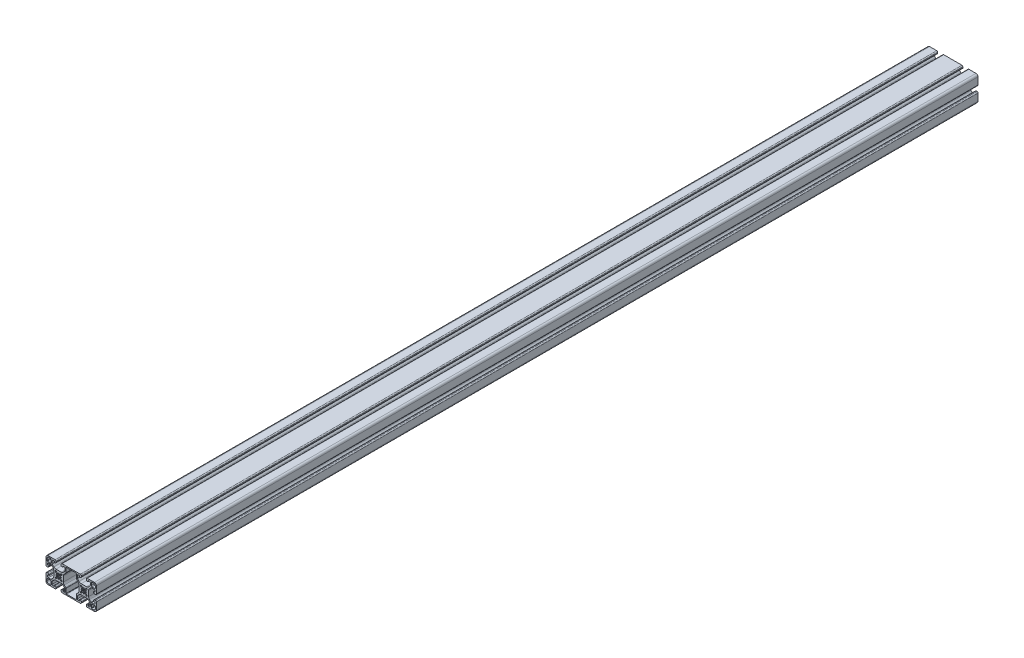
SolidWorks part; units mm, degrees
material "6105-T5 Aluminum"
ref_plane "Front Plane" through (0, 0, 0) normal (0, 0, 1) x (1, 0, 0)
ref_plane "Top Plane" through (0, 0, 0) normal (0, 1, 0) x (1, 0, 0)
ref_plane "Right Plane" through (0, 0, 0) normal (1, 0, 0) x (0, 0, -1)
sketch "Sketch1" plane through (0, 0, 0) normal (0, 0, 1) x (1, 0, 0)
  line L0 (-44, -18.4848) -> (-44, -17.255)
  line L1 (-46.474, -15.685) -> (-45.57, -15.685)
  line L2 (-56.83, -20) -> (-45.569, -20)
  line L3 (-46.855, -17.119) -> (-46.855, -16.066)
  line L4 (-60, -16.83) -> (-60, -5.57)
  line L5 (-49.015, -17.5) -> (-47.236, -17.5)
  line L6 (-58.43, -4) -> (-57.255, -4)
  line L7 (-50.285, -16.23) -> (-50.285, -12.2162)
  line L8 (-55.685, -5.57) -> (-55.685, -6.474)
  line L9 (-47.5137, -9.0762) -> (-50.0243, -11.5869)
  line L10 (-57.119, -6.855) -> (-56.066, -6.855)
  line L11 (-44.1549, -7.685) -> (-35.8451, -7.685)
  line L12 (-57.5, -9.015) -> (-57.5, -7.236)
  line L13 (-32.4863, -9.0762) -> (-29.9757, -11.5869)
  line L14 (-56.23, -10.285) -> (-52.2162, -10.285)
  line L15 (-29.715, -16.23) -> (-29.715, -12.2162)
  line L16 (-49.0762, -7.5137) -> (-51.5869, -10.0243)
  line L17 (-30.985, -17.5) -> (-32.764, -17.5)
  line L18 (-47.685, 4.1549) -> (-47.685, -4.1549)
  line L19 (-33.145, -17.119) -> (-33.145, -16.066)
  line L20 (-49.0762, 7.5137) -> (-51.5869, 10.0243)
  line L21 (-34.43, -15.685) -> (-33.526, -15.685)
  line L22 (-56.23, 10.285) -> (-52.2162, 10.285)
  line L23 (-36, -18.4848) -> (-36, -17.255)
  line L24 (-57.5, 9.015) -> (-57.5, 7.236)
  line L25 (-5.57, -20) -> (-34.431, -20)
  line L26 (-57.119, 6.855) -> (-56.066, 6.855)
  line L27 (-4, -17.255) -> (-4, -18.43)
  line L28 (-55.685, 6.474) -> (-55.685, 5.57)
  line L29 (-5.57, -15.685) -> (-6.474, -15.685)
  line L30 (-58.43, 4) -> (-57.255, 4)
  line L31 (-6.855, -17.119) -> (-6.855, -16.066)
  line L32 (-60, 16.83) -> (-60, 5.57)
  line L33 (-9.015, -17.5) -> (-7.236, -17.5)
  line L34 (-56.83, 20) -> (-45.57, 20)
  line L35 (-10.285, -16.23) -> (-10.285, -12.2162)
  line L36 (-44, 18.43) -> (-44, 17.255)
  line L37 (-7.5137, -9.0762) -> (-10.0243, -11.5869)
  line L38 (-45.57, 15.685) -> (-46.474, 15.685)
  line L39 (4.1549, -7.685) -> (-4.1549, -7.685)
  line L40 (-46.855, 17.119) -> (-46.855, 16.066)
  line L41 (7.5137, -9.0762) -> (10.0243, -11.5869)
  line L42 (-49.015, 17.5) -> (-47.236, 17.5)
  line L43 (10.285, -16.23) -> (10.285, -12.2162)
  line L44 (-50.285, 16.23) -> (-50.285, 12.2162)
  line L45 (9.015, -17.5) -> (7.236, -17.5)
  line L46 (-47.5137, 9.0762) -> (-50.0243, 11.5869)
  line L47 (6.855, -17.119) -> (6.855, -16.066)
  line L48 (-35.8451, 7.685) -> (-44.1549, 7.685)
  line L49 (6.474, -15.685) -> (5.57, -15.685)
  line L50 (-32.4863, 9.0762) -> (-29.9757, 11.5869)
  line L51 (4, -17.255) -> (4, -18.43)
  line L52 (-29.715, 16.23) -> (-29.715, 12.2162)
  line L53 (16.83, -20) -> (5.57, -20)
  line L54 (-30.985, 17.5) -> (-32.764, 17.5)
  line L55 (20, -16.83) -> (20, -5.57)
  line L56 (-33.145, 17.119) -> (-33.145, 16.066)
  line L57 (17.255, -4) -> (18.43, -4)
  line L58 (-33.526, 15.685) -> (-34.43, 15.685)
  line L59 (15.685, -5.57) -> (15.685, -6.474)
  line L60 (-36, 18.43) -> (-36, 17.255)
  line L61 (17.119, -6.855) -> (16.066, -6.855)
  line L62 (-34.43, 20) -> (-5.57, 20)
  line L63 (17.5, -9.015) -> (17.5, -7.236)
  line L64 (-4, 18.43) -> (-4, 17.255)
  line L65 (16.23, -10.285) -> (12.2162, -10.285)
  line L66 (-6.474, 15.685) -> (-5.57, 15.685)
  line L67 (9.0762, -7.5137) -> (11.5869, -10.0243)
  line L68 (-6.855, 17.119) -> (-6.855, 16.066)
  line L69 (7.685, 4.1549) -> (7.685, -4.1549)
  line L70 (-9.015, 17.5) -> (-7.236, 17.5)
  line L71 (9.0762, 7.5137) -> (11.5869, 10.0243)
  line L72 (-10.285, 16.23) -> (-10.285, 12.2162)
  line L73 (16.23, 10.285) -> (12.2162, 10.285)
  line L74 (-7.5137, 9.0762) -> (-10.0243, 11.5869)
  line L75 (17.5, 9.015) -> (17.5, 7.236)
  line L76 (-4.1549, 7.685) -> (4.1549, 7.685)
  line L77 (17.119, 6.855) -> (16.066, 6.855)
  line L78 (7.5137, 9.0762) -> (10.0243, 11.5869)
  line L79 (15.685, 6.474) -> (15.685, 5.57)
  line L80 (10.285, 16.23) -> (10.285, 12.2162)
  line L81 (17.255, 4) -> (18.43, 4)
  line L82 (9.015, 17.5) -> (7.236, 17.5)
  line L83 (20, 16.83) -> (20, 5.57)
  line L84 (6.855, 17.119) -> (6.855, 16.066)
  line L85 (16.83, 20) -> (5.57, 20)
  line L86 (5.57, 15.685) -> (6.474, 15.685)
  line L87 (4, 18.43) -> (4, 17.255)
  line L88 (15.545, -18.345) -> (12.4898, -18.345)
  line L89 (18.345, -12.4898) -> (18.345, -15.545)
  line L90 (11.8598, -17.715) -> (11.8598, -13.1298)
  line L91 (13.1298, -11.8598) -> (17.715, -11.8598)
  line L92 (-11.8598, 17.715) -> (-11.8598, 10.8233)
  line L93 (-11.4878, 9.9253) -> (-9.0762, 7.5137)
  line L94 (-27.5102, 18.345) -> (-12.4898, 18.345)
  line L95 (-7.685, 4.1549) -> (-7.685, -4.1549)
  line L96 (-28.1402, 10.8233) -> (-28.1402, 17.715)
  line L97 (-9.0762, -7.5137) -> (-11.4878, -9.9253)
  line L98 (-30.9238, 7.5137) -> (-28.5122, 9.9253)
  line L99 (-11.8598, -10.8233) -> (-11.8598, -17.715)
  line L100 (-32.315, -4.1549) -> (-32.315, 4.1549)
  line L101 (-12.4898, -18.345) -> (-27.5102, -18.345)
  line L102 (-28.5122, -9.9253) -> (-30.9238, -7.5137)
  line L103 (-28.1402, -17.715) -> (-28.1402, -10.8233)
  line L104 (-58.345, -15.545) -> (-58.345, -12.4898)
  line L105 (-52.4898, -18.345) -> (-55.545, -18.345)
  line L106 (-57.715, -11.8598) -> (-53.1298, -11.8598)
  line L107 (-51.8598, -13.1298) -> (-51.8598, -17.715)
  line L108 (-55.545, 18.345) -> (-52.4898, 18.345)
  line L109 (-58.345, 12.4898) -> (-58.345, 15.545)
  line L110 (-51.8598, 17.715) -> (-51.8598, 13.1298)
  line L111 (-53.1298, 11.8598) -> (-57.715, 11.8598)
  line L112 (18.345, 15.545) -> (18.345, 12.4898)
  line L113 (12.4898, 18.345) -> (15.545, 18.345)
  line L114 (17.715, 11.8598) -> (13.1298, 11.8598)
  line L115 (11.8598, 13.1298) -> (11.8598, 17.715)
  line L116 (-34.8737, -3.712) -> (-34.5607, -4.8481)
  line L117 (-36.9951, -1.5907) -> (-34.8737, -3.712)
  line L118 (-35.1519, -5.4393) -> (-36.288, -5.1263)
  line L119 (-36.288, -5.1263) -> (-38.4093, -3.0049)
  line L120 (-35.9124, -0.4923) -> (-36.6579, -0.625)
  line L121 (-39.375, -3.3421) -> (-39.5077, -4.0876)
  line L122 (-36.6579, 0.625) -> (-35.9124, 0.4923)
  line L123 (-40.4923, -4.0876) -> (-40.625, -3.3421)
  line L124 (-34.8737, 3.712) -> (-36.9951, 1.5907)
  line L125 (-34.5607, 4.8481) -> (-34.8737, 3.712)
  line L126 (-41.5907, -3.0049) -> (-43.712, -5.1263)
  line L127 (-43.712, -5.1263) -> (-44.8481, -5.4393)
  line L128 (-36.288, 5.1263) -> (-35.1519, 5.4393)
  line L129 (-38.4093, 3.0049) -> (-36.288, 5.1263)
  line L130 (-45.4393, -4.8481) -> (-45.1263, -3.712)
  line L131 (-45.1263, -3.712) -> (-43.0049, -1.5907)
  line L132 (-39.5077, 4.0876) -> (-39.375, 3.3421)
  line L133 (-43.3421, -0.625) -> (-44.0876, -0.4923)
  line L134 (-40.625, 3.3421) -> (-40.4923, 4.0876)
  line L135 (-44.0876, 0.4923) -> (-43.3421, 0.625)
  line L136 (-43.712, 5.1263) -> (-41.5907, 3.0049)
  line L137 (-44.8481, 5.4393) -> (-43.712, 5.1263)
  line L138 (-43.0049, 1.5907) -> (-45.1263, 3.712)
  line L139 (-45.1263, 3.712) -> (-45.4393, 4.8481)
  line L140 (5.1263, -3.712) -> (5.4393, -4.8481)
  line L141 (3.0049, -1.5907) -> (5.1263, -3.712)
  line L142 (4.8481, -5.4393) -> (3.712, -5.1263)
  line L143 (3.712, -5.1263) -> (1.5907, -3.0049)
  line L144 (4.0876, -0.4923) -> (3.3421, -0.625)
  line L145 (0.625, -3.3421) -> (0.4923, -4.0876)
  line L146 (3.3421, 0.625) -> (4.0876, 0.4923)
  line L147 (-0.4923, -4.0876) -> (-0.625, -3.3421)
  line L148 (5.1263, 3.712) -> (3.0049, 1.5907)
  line L149 (5.4393, 4.8481) -> (5.1263, 3.712)
  line L150 (-1.5907, -3.0049) -> (-3.712, -5.1263)
  line L151 (-3.712, -5.1263) -> (-4.8481, -5.4393)
  line L152 (3.712, 5.1263) -> (4.8481, 5.4393)
  line L153 (1.5907, 3.0049) -> (3.712, 5.1263)
  line L154 (-5.4393, -4.8481) -> (-5.1263, -3.712)
  line L155 (-5.1263, -3.712) -> (-3.0049, -1.5907)
  line L156 (0.4923, 4.0876) -> (0.625, 3.3421)
  line L157 (-3.3421, -0.625) -> (-4.0876, -0.4923)
  line L158 (-0.625, 3.3421) -> (-0.4923, 4.0876)
  line L159 (-4.0876, 0.4923) -> (-3.3421, 0.625)
  line L160 (-3.712, 5.1263) -> (-1.5907, 3.0049)
  line L161 (-4.8481, 5.4393) -> (-3.712, 5.1263)
  line L162 (-3.0049, 1.5907) -> (-5.1263, 3.712)
  line L163 (-5.1263, 3.712) -> (-5.4393, 4.8481)
  arc A0 (-44, -17.255) -> (-45.57, -15.685) centre (-45.57, -17.255) ccw
  arc A1 (-45.569, -20) -> (-44, -18.4848) centre (-45.569, -18.43) ccw
  arc A2 (-46.474, -15.685) -> (-46.855, -16.066) centre (-46.474, -16.066) ccw
  arc A3 (-60, -16.83) -> (-56.83, -20) centre (-56.83, -16.83) ccw
  arc A4 (-47.236, -17.5) -> (-46.855, -17.119) centre (-47.236, -17.119) ccw
  arc A5 (-58.43, -4) -> (-60, -5.57) centre (-58.43, -5.57) ccw
  arc A6 (-50.285, -16.23) -> (-49.015, -17.5) centre (-49.015, -16.23) ccw
  arc A7 (-55.685, -5.57) -> (-57.255, -4) centre (-57.255, -5.57) ccw
  arc A8 (-50.0243, -11.5869) -> (-50.285, -12.2162) centre (-49.395, -12.2162) ccw
  arc A9 (-56.066, -6.855) -> (-55.685, -6.474) centre (-56.066, -6.474) ccw
  arc A10 (-44.1549, -7.685) -> (-47.5137, -9.0762) centre (-44.1549, -12.435) ccw
  arc A11 (-57.119, -6.855) -> (-57.5, -7.236) centre (-57.119, -7.236) ccw
  arc A12 (-32.4863, -9.0762) -> (-35.8451, -7.685) centre (-35.8451, -12.435) ccw
  arc A13 (-57.5, -9.015) -> (-56.23, -10.285) centre (-56.23, -9.015) ccw
  arc A14 (-29.715, -12.2162) -> (-29.9757, -11.5869) centre (-30.605, -12.2162) ccw
  arc A15 (-52.2162, -10.285) -> (-51.5869, -10.0243) centre (-52.2162, -9.395) ccw
  arc A16 (-30.985, -17.5) -> (-29.715, -16.23) centre (-30.985, -16.23) ccw
  arc A17 (-49.0762, -7.5137) -> (-47.685, -4.1549) centre (-52.435, -4.1549) ccw
  arc A18 (-33.145, -17.119) -> (-32.764, -17.5) centre (-32.764, -17.119) ccw
  arc A19 (-47.685, 4.1549) -> (-49.0762, 7.5137) centre (-52.435, 4.1549) ccw
  arc A20 (-33.145, -16.066) -> (-33.526, -15.685) centre (-33.526, -16.066) ccw
  arc A21 (-51.5869, 10.0243) -> (-52.2162, 10.285) centre (-52.2162, 9.395) ccw
  arc A22 (-34.43, -15.685) -> (-36, -17.255) centre (-34.43, -17.255) ccw
  arc A23 (-56.23, 10.285) -> (-57.5, 9.015) centre (-56.23, 9.015) ccw
  arc A24 (-36, -18.4848) -> (-34.431, -20) centre (-34.431, -18.43) ccw
  arc A25 (-57.5, 7.236) -> (-57.119, 6.855) centre (-57.119, 7.236) ccw
  arc A26 (-5.57, -20) -> (-4, -18.43) centre (-5.57, -18.43) ccw
  arc A27 (-55.685, 6.474) -> (-56.066, 6.855) centre (-56.066, 6.474) ccw
  arc A28 (-4, -17.255) -> (-5.57, -15.685) centre (-5.57, -17.255) ccw
  arc A29 (-57.255, 4) -> (-55.685, 5.57) centre (-57.255, 5.57) ccw
  arc A30 (-6.474, -15.685) -> (-6.855, -16.066) centre (-6.474, -16.066) ccw
  arc A31 (-60, 5.57) -> (-58.43, 4) centre (-58.43, 5.57) ccw
  arc A32 (-7.236, -17.5) -> (-6.855, -17.119) centre (-7.236, -17.119) ccw
  arc A33 (-56.83, 20) -> (-60, 16.83) centre (-56.83, 16.83) ccw
  arc A34 (-10.285, -16.23) -> (-9.015, -17.5) centre (-9.015, -16.23) ccw
  arc A35 (-44, 18.43) -> (-45.57, 20) centre (-45.57, 18.43) ccw
  arc A36 (-10.0243, -11.5869) -> (-10.285, -12.2162) centre (-9.395, -12.2162) ccw
  arc A37 (-45.57, 15.685) -> (-44, 17.255) centre (-45.57, 17.255) ccw
  arc A38 (-4.1549, -7.685) -> (-7.5137, -9.0762) centre (-4.1549, -12.435) ccw
  arc A39 (-46.855, 16.066) -> (-46.474, 15.685) centre (-46.474, 16.066) ccw
  arc A40 (7.5137, -9.0762) -> (4.1549, -7.685) centre (4.1549, -12.435) ccw
  arc A41 (-46.855, 17.119) -> (-47.236, 17.5) centre (-47.236, 17.119) ccw
  arc A42 (10.285, -12.2162) -> (10.0243, -11.5869) centre (9.395, -12.2162) ccw
  arc A43 (-49.015, 17.5) -> (-50.285, 16.23) centre (-49.015, 16.23) ccw
  arc A44 (9.015, -17.5) -> (10.285, -16.23) centre (9.015, -16.23) ccw
  arc A45 (-50.285, 12.2162) -> (-50.0243, 11.5869) centre (-49.395, 12.2162) ccw
  arc A46 (6.855, -17.119) -> (7.236, -17.5) centre (7.236, -17.119) ccw
  arc A47 (-47.5137, 9.0762) -> (-44.1549, 7.685) centre (-44.1549, 12.435) ccw
  arc A48 (6.855, -16.066) -> (6.474, -15.685) centre (6.474, -16.066) ccw
  arc A49 (-35.8451, 7.685) -> (-32.4863, 9.0762) centre (-35.8451, 12.435) ccw
  arc A50 (5.57, -15.685) -> (4, -17.255) centre (5.57, -17.255) ccw
  arc A51 (-29.9757, 11.5869) -> (-29.715, 12.2162) centre (-30.605, 12.2162) ccw
  arc A52 (4, -18.43) -> (5.57, -20) centre (5.57, -18.43) ccw
  arc A53 (-29.715, 16.23) -> (-30.985, 17.5) centre (-30.985, 16.23) ccw
  arc A54 (16.83, -20) -> (20, -16.83) centre (16.83, -16.83) ccw
  arc A55 (-32.764, 17.5) -> (-33.145, 17.119) centre (-32.764, 17.119) ccw
  arc A56 (20, -5.57) -> (18.43, -4) centre (18.43, -5.57) ccw
  arc A57 (-33.526, 15.685) -> (-33.145, 16.066) centre (-33.526, 16.066) ccw
  arc A58 (17.255, -4) -> (15.685, -5.57) centre (17.255, -5.57) ccw
  arc A59 (-36, 17.255) -> (-34.43, 15.685) centre (-34.43, 17.255) ccw
  arc A60 (15.685, -6.474) -> (16.066, -6.855) centre (16.066, -6.474) ccw
  arc A61 (-34.43, 20) -> (-36, 18.43) centre (-34.43, 18.43) ccw
  arc A62 (17.5, -7.236) -> (17.119, -6.855) centre (17.119, -7.236) ccw
  arc A63 (-4, 18.43) -> (-5.57, 20) centre (-5.57, 18.43) ccw
  arc A64 (16.23, -10.285) -> (17.5, -9.015) centre (16.23, -9.015) ccw
  arc A65 (-5.57, 15.685) -> (-4, 17.255) centre (-5.57, 17.255) ccw
  arc A66 (11.5869, -10.0243) -> (12.2162, -10.285) centre (12.2162, -9.395) ccw
  arc A67 (-6.855, 16.066) -> (-6.474, 15.685) centre (-6.474, 16.066) ccw
  arc A68 (7.685, -4.1549) -> (9.0762, -7.5137) centre (12.435, -4.1549) ccw
  arc A69 (-6.855, 17.119) -> (-7.236, 17.5) centre (-7.236, 17.119) ccw
  arc A70 (9.0762, 7.5137) -> (7.685, 4.1549) centre (12.435, 4.1549) ccw
  arc A71 (-9.015, 17.5) -> (-10.285, 16.23) centre (-9.015, 16.23) ccw
  arc A72 (12.2162, 10.285) -> (11.5869, 10.0243) centre (12.2162, 9.395) ccw
  arc A73 (-10.285, 12.2162) -> (-10.0243, 11.5869) centre (-9.395, 12.2162) ccw
  arc A74 (17.5, 9.015) -> (16.23, 10.285) centre (16.23, 9.015) ccw
  arc A75 (-7.5137, 9.0762) -> (-4.1549, 7.685) centre (-4.1549, 12.435) ccw
  arc A76 (17.119, 6.855) -> (17.5, 7.236) centre (17.119, 7.236) ccw
  arc A77 (4.1549, 7.685) -> (7.5137, 9.0762) centre (4.1549, 12.435) ccw
  arc A78 (16.066, 6.855) -> (15.685, 6.474) centre (16.066, 6.474) ccw
  arc A79 (10.0243, 11.5869) -> (10.285, 12.2162) centre (9.395, 12.2162) ccw
  arc A80 (15.685, 5.57) -> (17.255, 4) centre (17.255, 5.57) ccw
  arc A81 (10.285, 16.23) -> (9.015, 17.5) centre (9.015, 16.23) ccw
  arc A82 (18.43, 4) -> (20, 5.57) centre (18.43, 5.57) ccw
  arc A83 (7.236, 17.5) -> (6.855, 17.119) centre (7.236, 17.119) ccw
  arc A84 (20, 16.83) -> (16.83, 20) centre (16.83, 16.83) ccw
  arc A85 (6.474, 15.685) -> (6.855, 16.066) centre (6.474, 16.066) ccw
  arc A86 (5.57, 20) -> (4, 18.43) centre (5.57, 18.43) ccw
  arc A87 (4, 17.255) -> (5.57, 15.685) centre (5.57, 17.255) ccw
  arc A88 (15.545, -18.345) -> (18.345, -15.545) centre (15.545, -15.545) ccw
  arc A89 (11.8598, -17.715) -> (12.4898, -18.345) centre (12.4898, -17.715) ccw
  arc A90 (18.345, -12.4898) -> (17.715, -11.8598) centre (17.715, -12.4898) ccw
  arc A91 (13.1298, -11.8598) -> (11.8598, -13.1298) centre (13.1298, -13.1298) ccw
  arc A92 (-11.8598, 10.8233) -> (-11.4878, 9.9253) centre (-10.5898, 10.8233) ccw
  arc A93 (-11.8598, 17.715) -> (-12.4898, 18.345) centre (-12.4898, 17.715) ccw
  arc A94 (-7.685, 4.1549) -> (-9.0762, 7.5137) centre (-12.435, 4.1549) ccw
  arc A95 (-27.5102, 18.345) -> (-28.1402, 17.715) centre (-27.5102, 17.715) ccw
  arc A96 (-9.0762, -7.5137) -> (-7.685, -4.1549) centre (-12.435, -4.1549) ccw
  arc A97 (-28.5122, 9.9253) -> (-28.1402, 10.8233) centre (-29.4102, 10.8233) ccw
  arc A98 (-11.4878, -9.9253) -> (-11.8598, -10.8233) centre (-10.5898, -10.8233) ccw
  arc A99 (-30.9238, 7.5137) -> (-32.315, 4.1549) centre (-27.565, 4.1549) ccw
  arc A100 (-12.4898, -18.345) -> (-11.8598, -17.715) centre (-12.4898, -17.715) ccw
  arc A101 (-32.315, -4.1549) -> (-30.9238, -7.5137) centre (-27.565, -4.1549) ccw
  arc A102 (-28.1402, -17.715) -> (-27.5102, -18.345) centre (-27.5102, -17.715) ccw
  arc A103 (-28.1402, -10.8233) -> (-28.5122, -9.9253) centre (-29.4102, -10.8233) ccw
  arc A104 (-58.345, -15.545) -> (-55.545, -18.345) centre (-55.545, -15.545) ccw
  arc A105 (-57.715, -11.8598) -> (-58.345, -12.4898) centre (-57.715, -12.4898) ccw
  arc A106 (-52.4898, -18.345) -> (-51.8598, -17.715) centre (-52.4898, -17.715) ccw
  arc A107 (-51.8598, -13.1298) -> (-53.1298, -11.8598) centre (-53.1298, -13.1298) ccw
  arc A108 (-55.545, 18.345) -> (-58.345, 15.545) centre (-55.545, 15.545) ccw
  arc A109 (-51.8598, 17.715) -> (-52.4898, 18.345) centre (-52.4898, 17.715) ccw
  arc A110 (-58.345, 12.4898) -> (-57.715, 11.8598) centre (-57.715, 12.4898) ccw
  arc A111 (-53.1298, 11.8598) -> (-51.8598, 13.1298) centre (-53.1298, 13.1298) ccw
  arc A112 (18.345, 15.545) -> (15.545, 18.345) centre (15.545, 15.545) ccw
  arc A113 (17.715, 11.8598) -> (18.345, 12.4898) centre (17.715, 12.4898) ccw
  arc A114 (12.4898, 18.345) -> (11.8598, 17.715) centre (12.4898, 17.715) ccw
  arc A115 (11.8598, 13.1298) -> (13.1298, 11.8598) centre (13.1298, 13.1298) ccw
  arc A116 (-35.1519, -5.4393) -> (-34.5607, -4.8481) centre (-35.0503, -4.9497) ccw
  arc A117 (-36.9951, -1.5907) -> (-36.6579, -0.625) centre (-40, 0) ccw
  arc A118 (-39.375, -3.3421) -> (-38.4093, -3.0049) centre (-40, 0) ccw
  arc A119 (-35.9124, -0.4923) -> (-35.9124, 0.4923) centre (-36, 0) ccw
  arc A120 (-40.4923, -4.0876) -> (-39.5077, -4.0876) centre (-40, -4) ccw
  arc A121 (-36.6579, 0.625) -> (-36.9951, 1.5907) centre (-40, 0) ccw
  arc A122 (-41.5907, -3.0049) -> (-40.625, -3.3421) centre (-40, 0) ccw
  arc A123 (-34.5607, 4.8481) -> (-35.1519, 5.4393) centre (-35.0503, 4.9497) ccw
  arc A124 (-45.4393, -4.8481) -> (-44.8481, -5.4393) centre (-44.9497, -4.9497) ccw
  arc A125 (-38.4093, 3.0049) -> (-39.375, 3.3421) centre (-40, 0) ccw
  arc A126 (-43.3421, -0.625) -> (-43.0049, -1.5907) centre (-40, 0) ccw
  arc A127 (-39.5077, 4.0876) -> (-40.4923, 4.0876) centre (-40, 4) ccw
  arc A128 (-44.0876, 0.4923) -> (-44.0876, -0.4923) centre (-44, 0) ccw
  arc A129 (-40.625, 3.3421) -> (-41.5907, 3.0049) centre (-40, 0) ccw
  arc A130 (-43.0049, 1.5907) -> (-43.3421, 0.625) centre (-40, 0) ccw
  arc A131 (-44.8481, 5.4393) -> (-45.4393, 4.8481) centre (-44.9497, 4.9497) ccw
  arc A132 (4.8481, -5.4393) -> (5.4393, -4.8481) centre (4.9497, -4.9497) ccw
  arc A133 (3.0049, -1.5907) -> (3.3421, -0.625) centre (0, 0) ccw
  arc A134 (0.625, -3.3421) -> (1.5907, -3.0049) centre (0, 0) ccw
  arc A135 (4.0876, -0.4923) -> (4.0876, 0.4923) centre (4, 0) ccw
  arc A136 (-0.4923, -4.0876) -> (0.4923, -4.0876) centre (0, -4) ccw
  arc A137 (3.3421, 0.625) -> (3.0049, 1.5907) centre (0, 0) ccw
  arc A138 (-1.5907, -3.0049) -> (-0.625, -3.3421) centre (0, 0) ccw
  arc A139 (5.4393, 4.8481) -> (4.8481, 5.4393) centre (4.9497, 4.9497) ccw
  arc A140 (-5.4393, -4.8481) -> (-4.8481, -5.4393) centre (-4.9497, -4.9497) ccw
  arc A141 (1.5907, 3.0049) -> (0.625, 3.3421) centre (0, 0) ccw
  arc A142 (-3.3421, -0.625) -> (-3.0049, -1.5907) centre (0, 0) ccw
  arc A143 (0.4923, 4.0876) -> (-0.4923, 4.0876) centre (0, 4) ccw
  arc A144 (-4.0876, 0.4923) -> (-4.0876, -0.4923) centre (-4, 0) ccw
  arc A145 (-0.625, 3.3421) -> (-1.5907, 3.0049) centre (0, 0) ccw
  arc A146 (-3.0049, 1.5907) -> (-3.3421, 0.625) centre (0, 0) ccw
  arc A147 (-4.8481, 5.4393) -> (-5.4393, 4.8481) centre (-4.9497, 4.9497) ccw
extrude "Extrude1" add sketch "Sketch1" against normal blind 1400
